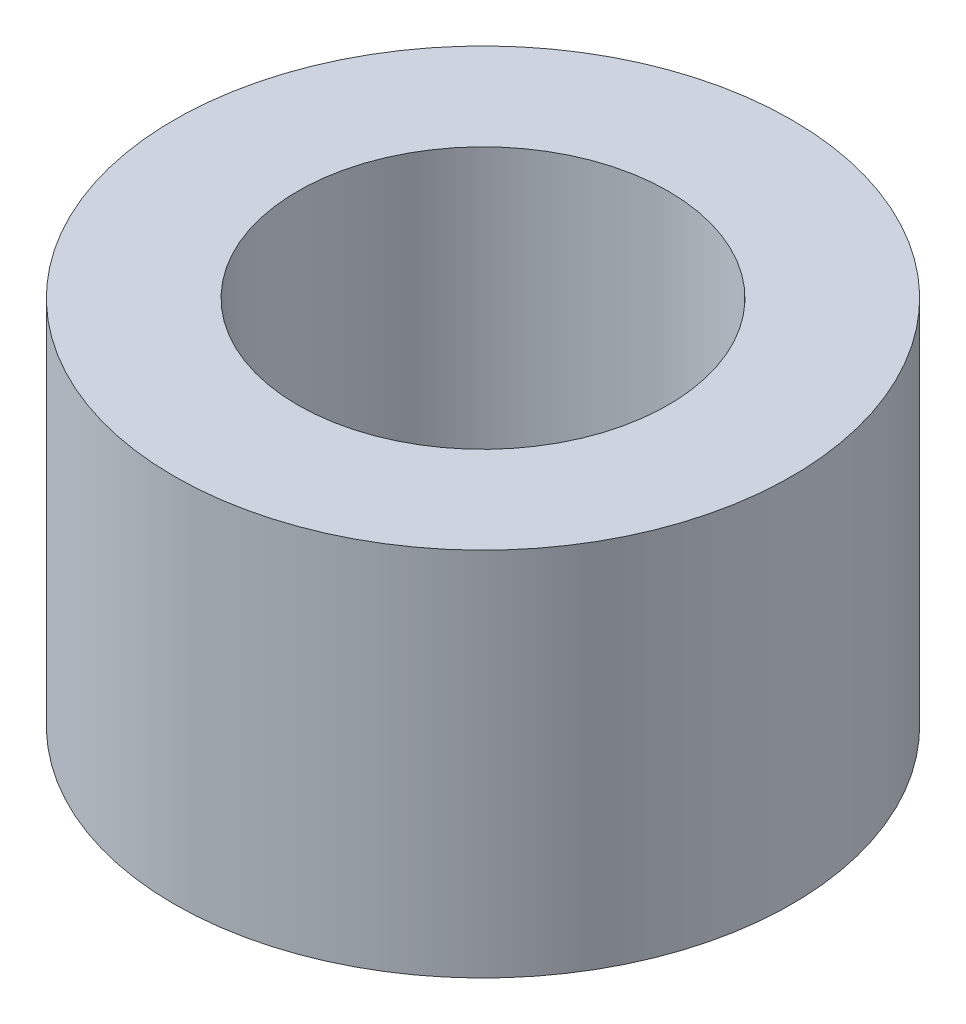
SolidWorks part; units mm, degrees
ref_plane "Front Plane" through (0, 0, 0) normal (0, 0, 1) x (1, 0, 0)
ref_plane "Top Plane" through (0, 0, 0) normal (0, 1, 0) x (1, 0, 0)
ref_plane "Right Plane" through (0, 0, 0) normal (1, 0, 0) x (0, 0, -1)
sketch "Sketch1" plane through (0, 0, 0) normal (0, 1, 0) x (1, 0, 0)
  circle A0 centre (0, 0) radius 1.905
  circle A1 centre (0, 0) radius 3.175
  dimension "D1" = 3.81
  dimension "D2" = 1.27
extrude "Boss-Extrude1" add sketch "Sketch1" along normal blind 15.24
sketch "Sketch2" plane through (0, 15.24, 0) normal (0, 1, 0) x (1, 0, 0)
  circle A0 centre (0, 0) radius 3.6012
extrude "Cut-Extrude1" cut sketch "Sketch2" against normal offset from surface (11.43 mm away) 3.81 up to face at (0, 0, 3.175)
